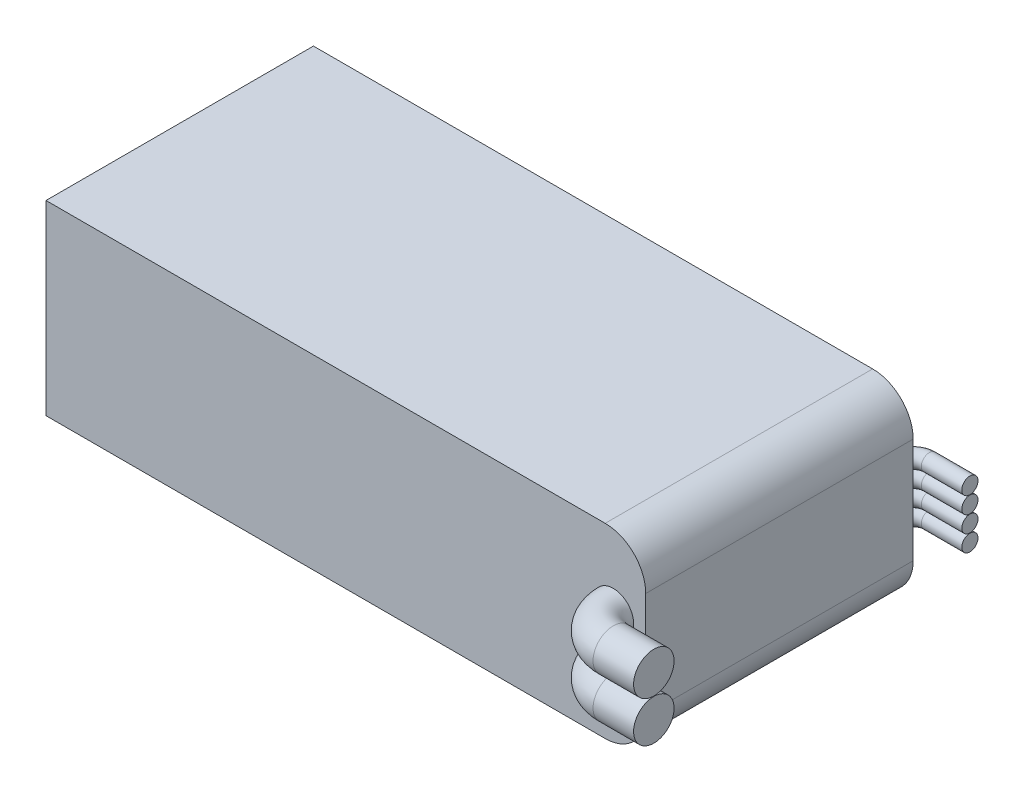
SolidWorks part; units mm, degrees
ref_plane "Front Plane" through (0, 0, 0) normal (0, 0, 1) x (1, 0, 0)
ref_plane "Top Plane" through (0, 0, 0) normal (0, 1, 0) x (1, 0, 0)
ref_plane "Right Plane" through (0, 0, 0) normal (1, 0, 0) x (0, 0, -1)
sketch "Sketch1" plane through (0, 0, 0) normal (0, 1, 0) x (1, 0, 0)
  line L1 (-37, -16.5) -> (37, -16.5)
  line L2 (-37, -16.5) -> (-37, 16.5)
  line L3 (-37, 16.5) -> (37, 16.5)
  line L4 (37, -16.5) -> (37, 16.5)
  line L5 (-37, -16.5) -> (37, 16.5) construction
  line L6 (-37, 16.5) -> (37, -16.5) construction
  point P0 (0, 0)
  dimension "D1" = 33
  dimension "D2" = 74
extrude "Boss-Extrude1" add sketch "Sketch1" along normal blind 23
fillet "Fillet1" radius 5 2 edges at (37, 0, 0) (37, 23, 0)
sketch "Sketch2" plane through (0, 0, 16.5) normal (0, 0, 1) x (1, 0, 0)
  line L0 (37, 18) -> (37, 5) construction
  line L1 (-37, 0) -> (32, 0) construction
  circle A0 centre (33, 14.05) radius 2.5
  circle A1 centre (33, 9) radius 2.5
  point P4 (31.5247, 7.7059)
  point P5 (31.1308, 16.3072)
  point P6 (0, 0)
  point P9 (33, 9.0659)
  dimension "D1" = 5
  dimension "D2" = 5
  dimension "D3" = 4
  dimension "D4" = 5.05
  dimension "D5" = 9
sketch "Sketch7" plane through (0, 0, 0) normal (0, -1, 0) x (-1, 0, 0)
  line L1 (-37, -20.5) -> (-42, -20.5)
  line L3 (37, -16.5) -> (-32, -16.5) construction
  arc A0 (-37, -20.5) -> (-33, -16.5) centre (-37, -16.5) ccw
  point P0 (-45.5475, -21.5)
  dimension "D1" = 4
  dimension "D2" = 5
sweep "Sweep5" add profiles "Sketch2" path "Sketch7"
sketch "Sketch9" plane through (0, 0, -16.5) normal (0, 0, -1) x (-1, 0, 0)
  line L0 (-37, 11.5) -> (37, 11.5) construction
  line L1 (-37, 18) -> (-37, 5) construction
  line L2 (37, 23) -> (37, 0) construction
  circle A0 centre (-35, 12.52) radius 1
  circle A1 centre (-35, 10.48) radius 1
  circle A2 centre (-35, 14.56) radius 1
  circle A3 centre (-35, 8.44) radius 1
  point P6 (0, 0)
  dimension "D1" = 2
  dimension "D4" = 2
  dimension "D6" = 2
  dimension "D8" = 2
  dimension "D2" = 2
  dimension "D3" = 1.02
  dimension "D5" = 1.02
  dimension "D7" = 2.04
  dimension "D9" = 2.04
sketch "Sketch10" plane through (0, 0, 0) normal (0, 1, 0) x (1, 0, 0)
  line L0 (36, 16.5) -> (34, 16.5) construction
  line L2 (37, 18.5) -> (42, 18.5)
  line L3 (37, 16.5) -> (-37, 16.5) construction
  line L4 (42, -23) -> (42, -18) construction
  arc A0 (35, 16.5) -> (37, 18.5) centre (37, 16.5) cw
  point P0 (40.602, 18.5)
  point P8 (0, 0)
  dimension "D1" = 2
sweep "Sweep6" add profiles "Sketch9" path "Sketch10"
